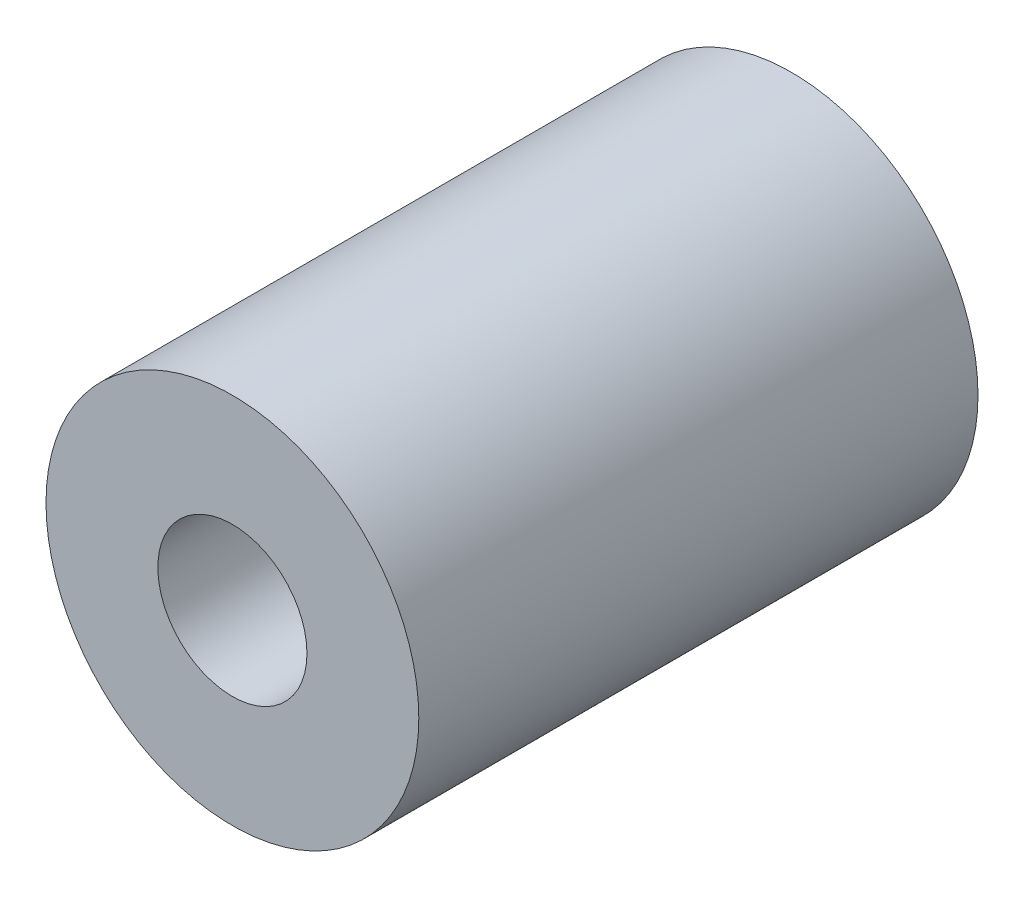
SolidWorks part; units mm, degrees
material "1060 合金"
ref_plane "正面" through (0, 0, 0) normal (0, 0, 1) x (1, 0, 0)
ref_plane "平面" through (0, 0, 0) normal (0, 1, 0) x (1, 0, 0)
ref_plane "右側面" through (0, 0, 0) normal (1, 0, 0) x (0, 0, -1)
sketch "ｽｹｯﾁ1" plane through (0, 0, 0) normal (0, 0, 1) x (1, 0, 0)
  circle A0 centre (0, 0) radius 4
  circle A1 centre (0, 0) radius 1.6
  dimension "D1" = 8
  dimension "D2" = 3.2
extrude "ﾎﾞｽ - 押し出し1" add sketch "ｽｹｯﾁ1" along normal blind 12
